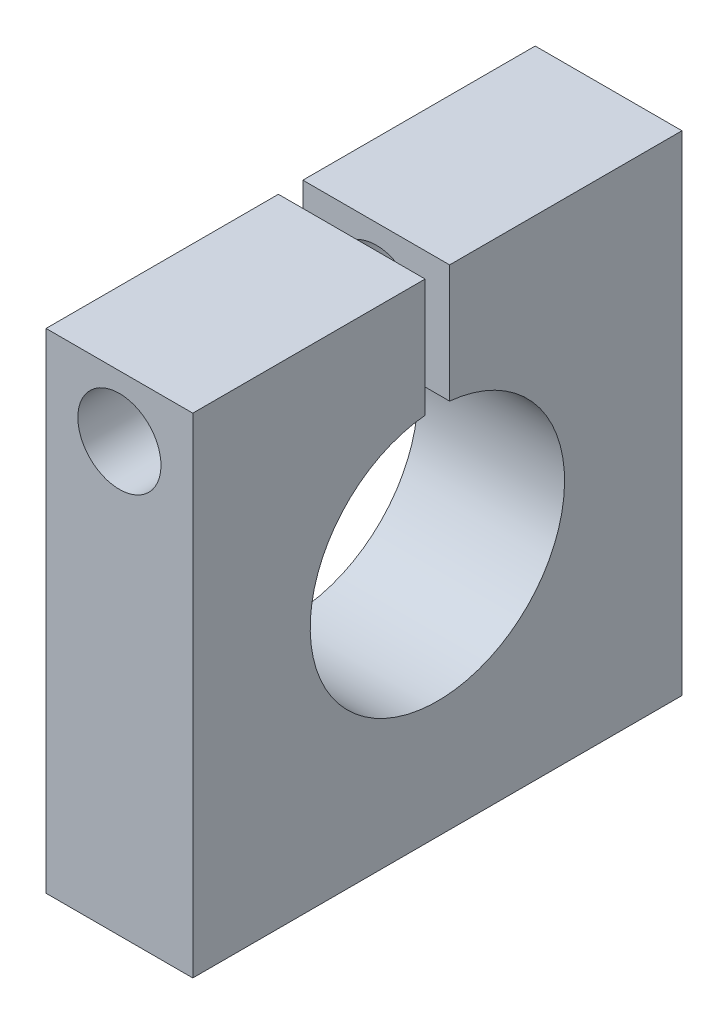
SolidWorks part; units mm, degrees
ref_plane "Front" through (0, 0, 0) normal (0, 0, 1) x (1, 0, 0)
ref_plane "Top" through (0, 0, 0) normal (0, 1, 0) x (1, 0, 0)
ref_plane "Right" through (0, 0, 0) normal (1, 0, 0) x (0, 0, -1)
sketch "Sketch1" plane through (0, 0, 0) normal (1, 0, 0) x (0, 0, -1)
  line L0 (-0.5, 10) -> (-0.5, 5.1759)
  line L1 (-10, 10) -> (10, 10)
  line L2 (-10, 10) -> (-10, -10)
  line L3 (-10, -10) -> (10, -10)
  line L4 (10, 10) -> (10, -10)
  line L5 (-10, 10) -> (10, -10) construction
  line L6 (-10, -10) -> (10, 10) construction
  line L7 (0.5, 10) -> (0.5, 5.1759)
  circle A0 centre (0, 0) radius 5.2
  point P0 (0, 0)
  dimension "D1" = 20
  dimension "D3" = 10.4
  dimension "D2" = 20
  dimension "D4" = 9.5
  dimension "D5" = 9.5
extrude "Boss-Extrude1" add sketch "Sketch1" along normal blind 6 contours A0 L0 L1 L2 L3 L4 L7
sketch "Sketch2" plane through (0, 0, -10) normal (0, 0, -1) x (-1, 0, 0)
  line L0 (-3, 10) -> (-3, 7.5)
  line L1 (-6, 10) -> (0, 10) construction
  circle A0 centre (-3, 7.5) radius 1.7
  dimension "D1" = 2.5
extrude "Cut-Extrude1" cut sketch "Sketch2" against normal through all
